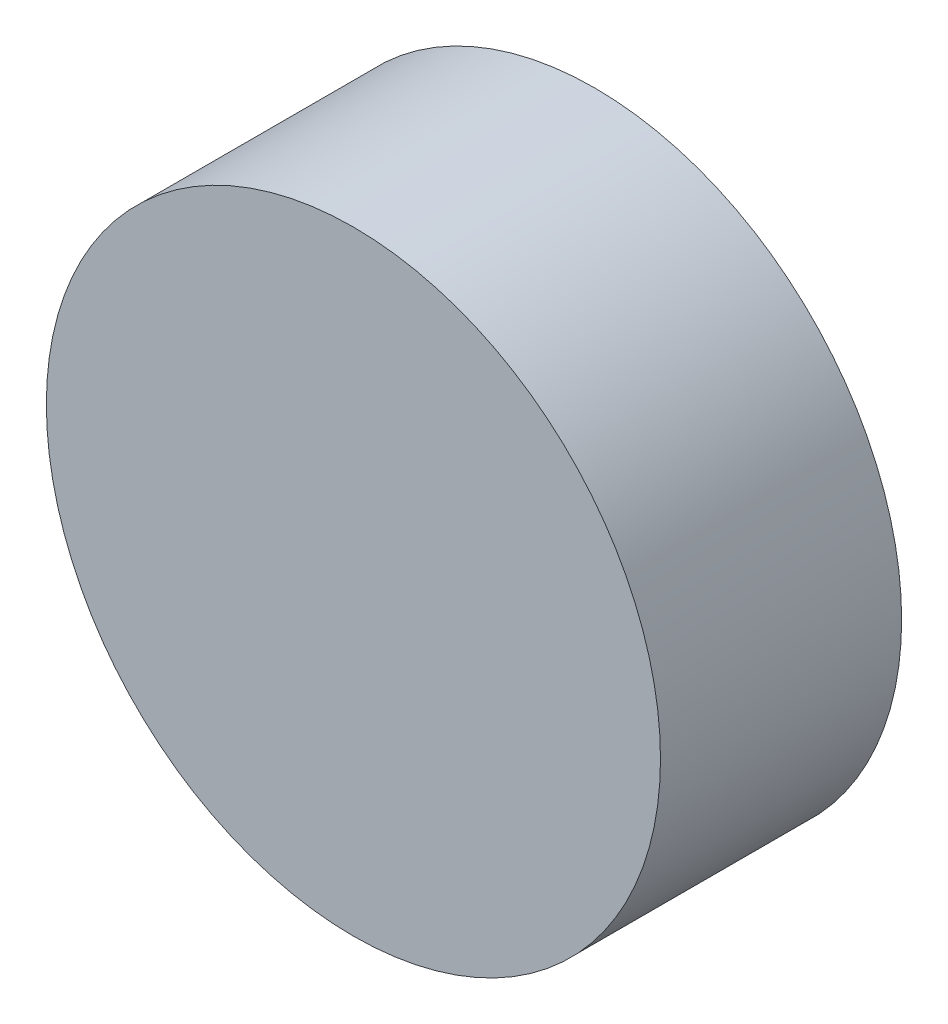
SolidWorks part; units mm, degrees
ref_plane "Front Plane" through (0, 0, 0) normal (0, 0, 1) x (1, 0, 0)
ref_plane "Top Plane" through (0, 0, 0) normal (0, 1, 0) x (1, 0, 0)
ref_plane "Right Plane" through (0, 0, 0) normal (1, 0, 0) x (0, 0, -1)
sketch "Sketch1" plane through (0, 0, 0) normal (0, 0, 1) x (1, 0, 0)
  circle A0 centre (0, 0) radius 34
  dimension "D1" = 68
extrude "Boss-Extrude1" add sketch "Sketch1" along normal blind 26.7
